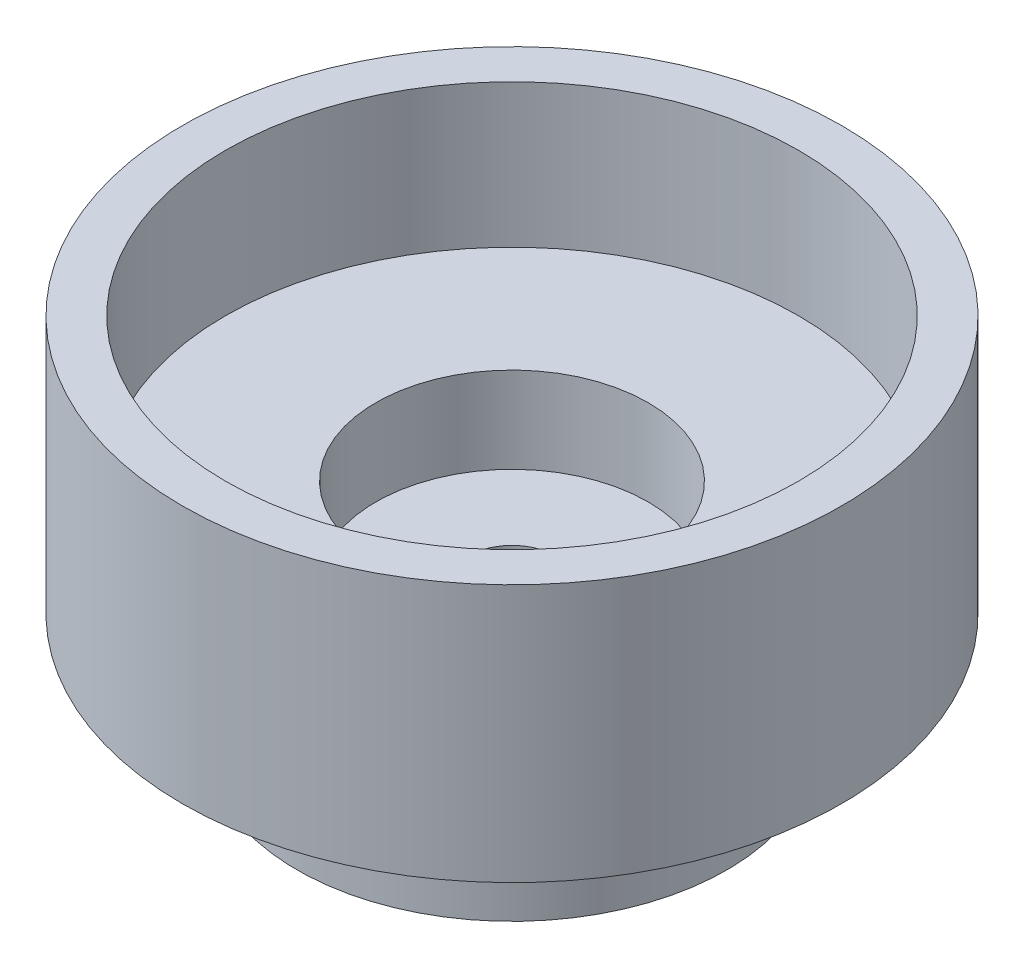
SolidWorks part; units mm, degrees
ref_plane "정면" through (0, 0, 0) normal (0, 0, 1) x (1, 0, 0)
ref_plane "윗면" through (0, 0, 0) normal (0, 1, 0) x (1, 0, 0)
ref_plane "우측면" through (0, 0, 0) normal (1, 0, 0) x (0, 0, -1)
sketch "스케치1" plane through (0, 0, 0) normal (0, 1, 0) x (1, 0, 0)
  circle A0 centre (0, 0) radius 23
  dimension "D1" = 46
extrude "보스-돌출1" add sketch "스케치1" along normal blind 26
sketch "스케치7" plane through (0, 0, 0) normal (0, -1, 0) x (-1, 0, 0)
  circle A0 centre (0, 0) radius 23
  circle A1 centre (0, 0) radius 15
extrude "컷-돌출5" cut sketch "스케치7" against normal blind 8
sketch "스케치8" plane through (0, 0, 0) normal (0, -1, 0) x (1, 0, 0)
  circle A0 centre (0, 0) radius 9.5
extrude "컷-돌출6" cut sketch "스케치8" against normal blind 6 contours A0
sketch "스케치9" plane through (0, 26, 0) normal (0, 1, 0) x (1, 0, 0)
  circle A0 centre (0, 0) radius 3
extrude "컷-돌출7" cut sketch "스케치9" against normal blind 24.5
sketch "스케치10" plane through (0, 26, 0) normal (0, 1, 0) x (1, 0, 0)
  circle A0 centre (0, 0) radius 20
extrude "컷-돌출8" cut sketch "스케치10" against normal blind 10
sketch "스케치11" plane through (0, 16, 0) normal (0, 1, 0) x (1, 0, 0)
  circle A0 centre (0, 0) radius 9.5
extrude "컷-돌출10" cut sketch "스케치11" against normal blind 6
